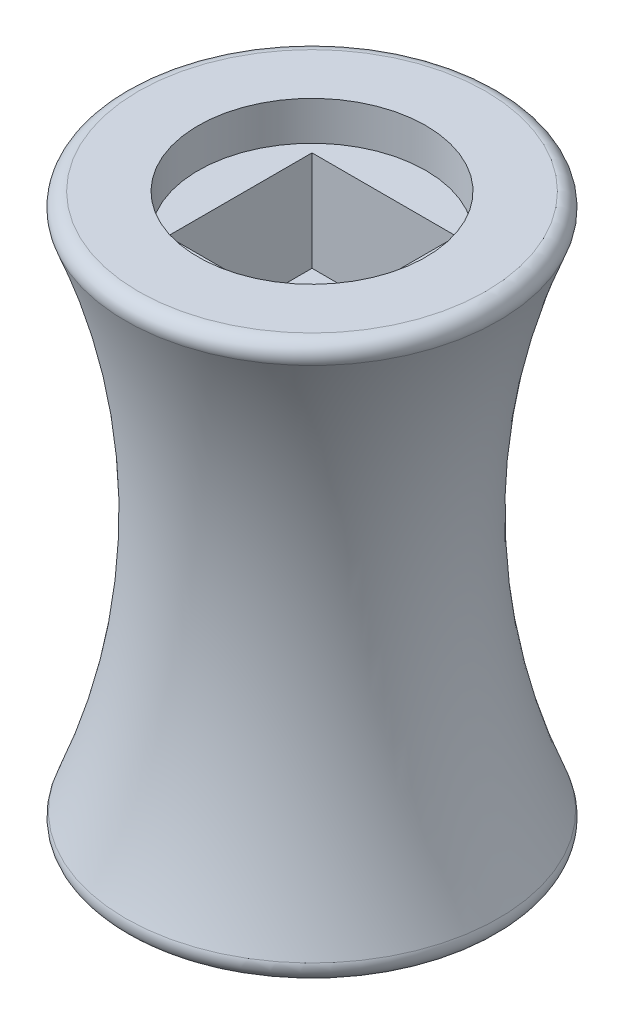
SolidWorks part; units mm, degrees
ref_plane "Front Plane" through (0, 0, 0) normal (0, 0, 1) x (1, 0, 0)
ref_plane "Top Plane" through (0, 0, 0) normal (0, 1, 0) x (1, 0, 0)
ref_plane "Right Plane" through (0, 0, 0) normal (1, 0, 0) x (0, 0, -1)
sketch "Sketch1" plane through (0, 0, 0) normal (1, 0, 0) x (0, 0, -1)
  line L0 (0, 0) -> (0, 25.4) construction
  line L1 (2.54, 0) -> (2.54, 25.4)
  line L2 (2.54, 25.4) -> (8.89, 25.4)
  line L3 (2.54, 0) -> (8.89, 0)
  arc A0 (8.89, 25.4) -> (8.89, 0) centre (37.9894, 12.7) ccw
  point P7 (0, 0)
  dimension "D3" = 31.75
  dimension "D1" = 25.4
  dimension "D2" = 5.08
  dimension "D4" = 8.89
revolve "Revolve1" add sketch "Sketch1" angle 360 about L0
sketch "Sketch2" plane through (0, 0, 0) normal (0, -1, 0) x (1, 0, 0)
  line L1 (-3.302, -3.302) -> (3.302, -3.302)
  line L2 (-3.302, -3.302) -> (-3.302, 3.302)
  line L3 (-3.302, 3.302) -> (3.302, 3.302)
  line L4 (3.302, -3.302) -> (3.302, 3.302)
  line L5 (-3.302, -3.302) -> (3.302, 3.302) construction
  line L6 (-3.302, 3.302) -> (3.302, -3.302) construction
  point P0 (0, 0)
  dimension "D1" = 6.604
extrude "Cut-Extrude1" cut sketch "Sketch2" against normal through all
sketch "Sketch3" plane through (0, 0, 0) normal (0, -1, 0) x (1, 0, 0)
  circle A0 centre (0, 0) radius 5.207
  dimension "D1" = 10.414
extrude "Cut-Extrude2" cut sketch "Sketch3" against normal blind 1.778
ref_plane "Plane1" through (0, 12.7, 0) normal (0, -1, 0) x (-1, 0, 0)
fillet "Fillet1" radius 0.635 2 edges at (0, 0, -8.89) (0, 25.4, -8.89)
mirror "Mirror1" about plane through (0, 12.7, 0) normal (0, -1, 0) of "Cut-Extrude2"
sketch "Sketch4" plane through (0, 12.7, 0) normal (0, -1, 0) x (-1, 0, 0)
  line L1 (3.302, -3.302) -> (-3.302, -3.302)
  line L2 (3.302, -3.302) -> (3.302, 3.302)
  line L3 (3.302, 3.302) -> (-3.302, 3.302)
  line L4 (-3.302, -3.302) -> (-3.302, 3.302)
  line L5 (3.302, -3.302) -> (-3.302, 3.302) construction
  line L6 (3.302, 3.302) -> (-3.302, -3.302) construction
  circle A0 centre (0, 0) radius 2.54
  dimension "D1" = 5.08
extrude "Boss-Extrude1" add sketch "Sketch4" along normal mid plane 12.7
